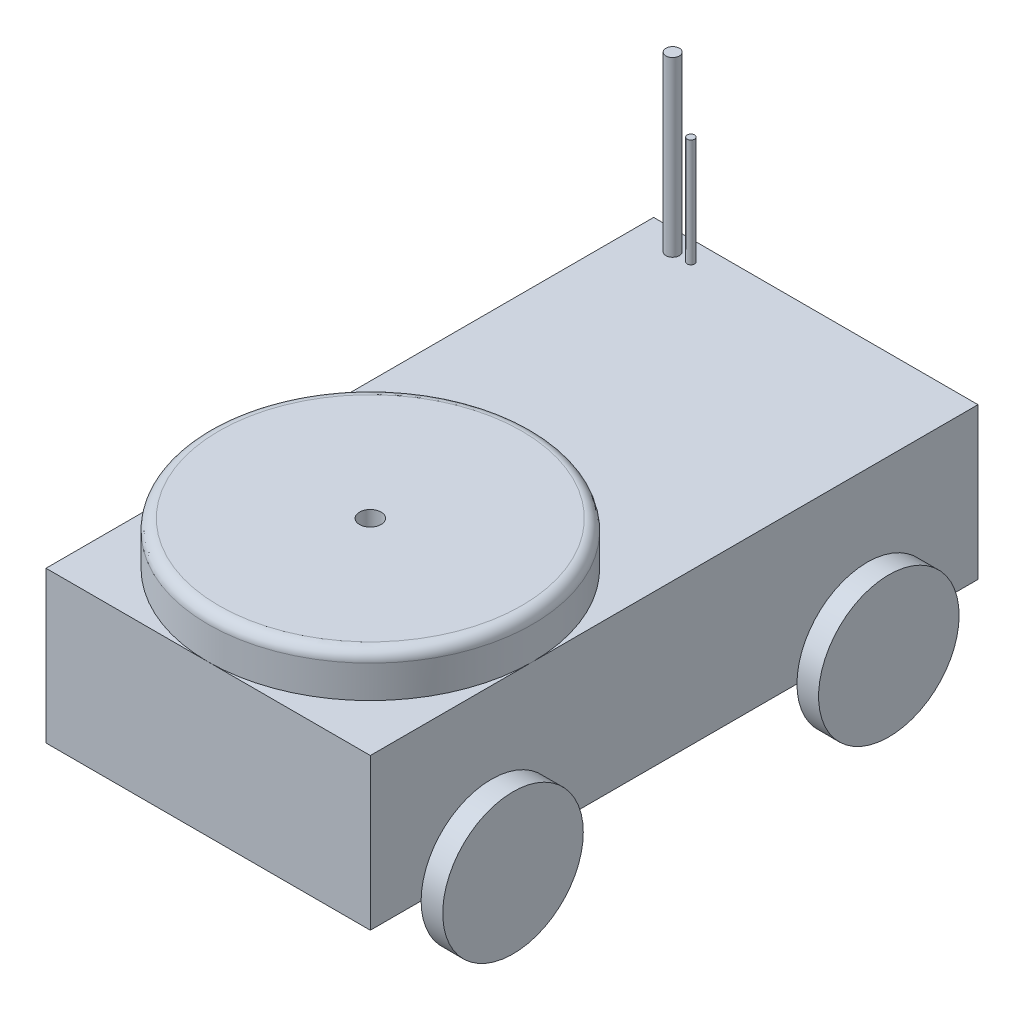
SolidWorks part; units mm, degrees
ref_plane "Front Plane" through (0, 0, 0) normal (0, 0, 1) x (1, 0, 0)
ref_plane "Top Plane" through (0, 0, 0) normal (0, 1, 0) x (1, 0, 0)
ref_plane "Right Plane" through (0, 0, 0) normal (1, 0, 0) x (0, 0, -1)
sketch "Sketch1" plane through (0, 0, 0) normal (0, 1, 0) x (1, 0, 0)
  circle A0 centre (0, 0) radius 75
  dimension "D1" = 150
extrude "Boss-Extrude1" add sketch "Sketch1" along normal blind 20
fillet "Fillet4" radius 5 1 edges at (0, 20, 75)
sketch "Sketch2" plane through (0, 0, 0) normal (0, 1, 0) x (1, 0, 0)
  circle A0 centre (0, 0) radius 5
  dimension "D1" = 10
extrude "Cut-Extrude1" cut sketch "Sketch2" along normal blind 10 from offset 10
sketch "Sketch3" plane through (0, 0, 0) normal (0, -1, 0) x (1, 0, 0)
  line L0 (0, 0) -> (-117.6061, 0) construction
  line L1 (-117.6061, 0) -> (158.8636, 0) construction
  line L2 (0, -75) -> (0, 75) construction
  line L3 (0, 75) -> (75, 75) construction
  line L4 (75, 75) -> (75, -75) construction
  line L5 (75, -75) -> (0, -75) construction
  line L6 (0, -75) -> (-75, -75) construction
  line L7 (-75, -75) -> (-75, 75) construction
  line L8 (-75, 75) -> (0, 75) construction
  line L10 (-75, 75) -> (75, 75)
  line L11 (-75, 75) -> (-75, -206.0354)
  line L12 (-75, -206.0354) -> (75, -206.0354)
  line L13 (75, 75) -> (75, -206.0354)
  circle A0 centre (0, 0) radius 75 construction
extrude "Boss-Extrude2" add sketch "Sketch3" along normal blind 70
sketch "Sketch4" plane through (-75, 0, 0) normal (-1, 0, 0) x (0, 0, 1)
  line L1 (75, -70) -> (-206.0354, -70) construction
  circle A2 centre (21.1645, -70) radius 32.5
  circle A3 centre (-154.8027, -70) radius 32.5
  dimension "D1" = 65
  dimension "D2" = 65
extrude "Boss-Extrude3" add sketch "Sketch4" along normal blind 10 contours A3
sketch "Sketch6" plane through (-75, 0, 0) normal (-1, 0, 0) x (0, 0, 1)
  line L0 (75, -70) -> (-122.3027, -70) construction
  circle A0 centre (19.0163, -70) radius 32.5
  dimension "D1" = 65
extrude "Boss-Extrude4" add sketch "Sketch6" along normal blind 10
sketch "Sketch8" plane through (75, 0, 0) normal (1, 0, 0) x (0, 0, -1)
  line L0 (-51.5163, -70) -> (13.4837, -70) construction
  circle A0 centre (-19.0163, -70) radius 32.5
  dimension "D1" = 65
extrude "Boss-Extrude5" add sketch "Sketch8" along normal blind 10
sketch "Sketch9" plane through (75, 0, 0) normal (1, 0, 0) x (0, 0, -1)
  line L0 (122.3027, -70) -> (187.3027, -70) construction
  circle A0 centre (154.8027, -70) radius 32.5
  dimension "D1" = 65
extrude "Boss-Extrude6" add sketch "Sketch9" along normal blind 10
sketch "Sketch10" plane through (0, 0, 0) normal (0, 1, 0) x (1, 0, 0)
  circle A0 centre (-56.8266, 196.6585) radius 3.1099
extrude "Boss-Extrude7" add sketch "Sketch10" along normal blind 80
sketch "Sketch11" plane through (0, 0, 0) normal (0, 1, 0) x (1, 0, 0)
  circle A0 centre (-48.5777, 196.8522) radius 1.7215
extrude "Boss-Extrude8" add sketch "Sketch11" along normal blind 50
